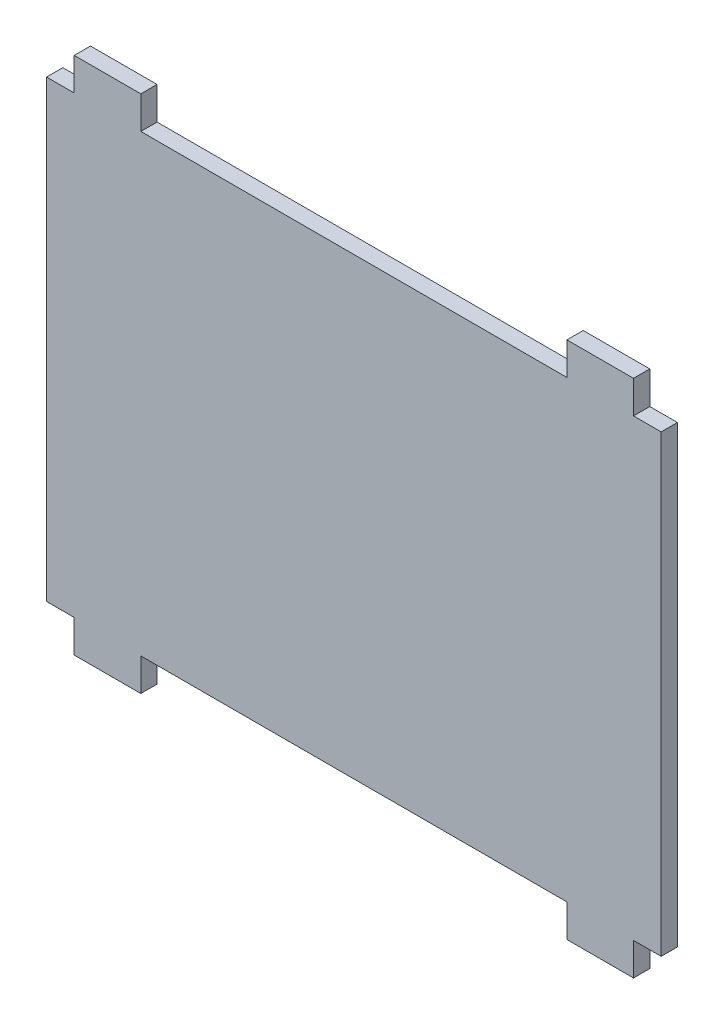
SolidWorks part; units mm, degrees
ref_plane "Front Plane" through (0, 0, 0) normal (0, 0, 1) x (1, 0, 0)
ref_plane "Top Plane" through (0, 0, 0) normal (0, 1, 0) x (1, 0, 0)
ref_plane "Right Plane" through (0, 0, 0) normal (1, 0, 0) x (0, 0, -1)
sketch "Sketch1" plane through (0, 0, 0) normal (0, 0, 1) x (1, 0, 0)
  line L0 (0.8731, 0) -> (-0.8731, 0) construction
  line L1 (-30, 0) -> (30, 0)
  line L2 (-30, 0) -> (-30, 25.35)
  line L3 (-30, 25.35) -> (30, 25.35)
  line L4 (30, 0) -> (30, 25.35)
  line L5 (0, -0.8731) -> (0, 0.8731) construction
  point P6 (0, 25.35)
  dimension "D1" = 60
  dimension "D2" = 25.35
extrude "Boss-Extrude1" add sketch "Sketch1" along normal blind 1.5875
sketch "Sketch2" plane through (0, 0, 1.5875) normal (0, 0, 1) x (1, 0, 0)
  line L0 (30, 25.35) -> (-30, 25.35) construction
  line L1 (-3.3, 25.35) -> (3.3, 25.35) construction
  line L2 (-3.3, 25.35) -> (-3.3, 22.225) construction
  line L3 (-3.3, 22.225) -> (3.3, 22.225) construction
  line L4 (3.3, 25.35) -> (3.3, 22.225) construction
  line L5 (0, -0.8731) -> (0, 0.8731) construction
  line L22 (-20.8, 25.35) -> (20.8, 25.35)
  line L27 (-20.8, 25.35) -> (-20.8, 22.17)
  line L28 (-20.8, 22.17) -> (20.8, 22.17)
  line L29 (20.8, 25.35) -> (20.8, 22.17)
  line L30 (27.3, 25.35) -> (32.7, 25.35)
  line L31 (27.3, 25.35) -> (27.3, 22.17)
  line L32 (27.3, 22.17) -> (32.7, 22.17)
  line L33 (32.7, 25.35) -> (32.7, 22.17)
  line L42 (-32.7, 25.35) -> (-27.3, 25.35)
  line L43 (-32.7, 25.35) -> (-32.7, 22.17)
  line L44 (-32.7, 22.17) -> (-27.3, 22.17)
  line L45 (-27.3, 25.35) -> (-27.3, 22.17)
  point P6 (0, 25.35)
  dimension "D1" = 6.6
  dimension "D2" = 3.18
  dimension "D3" = 6.5
  dimension "D4" = 6.5
  dimension "D5" = 3.18
  dimension "D6" = 3.18
extrude "Cut-Extrude1" cut sketch "Sketch2" against normal blind 1.5875
mirror "Mirror1" about plane through (0, 0, 0) normal (0, 1, 0) of "Cut-Extrude1", "Boss-Extrude1"
